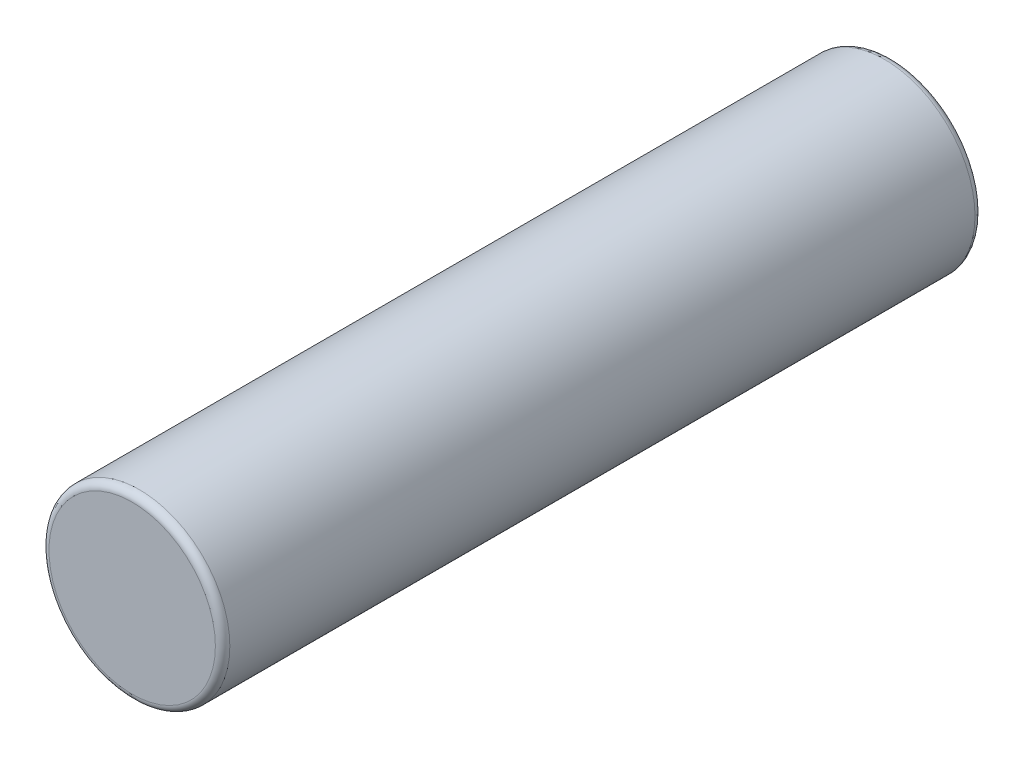
SolidWorks part; units mm, degrees
ref_plane "Face" through (0, 0, 0) normal (0, 0, 1) x (1, 0, 0)
ref_plane "Dessus" through (0, 0, 0) normal (0, 1, 0) x (1, 0, 0)
ref_plane "Droite" through (0, 0, 0) normal (1, 0, 0) x (0, 0, -1)
sketch "Esquisse1" plane through (0, 0, 0) normal (0, 0, 1) x (1, 0, 0)
  circle A0 centre (0, 0) radius 2.5
  dimension "D1" = 5
extrude "Extrusion1" add sketch "Esquisse1" along normal mid plane 21
fillet "Congé1" radius 0.2
